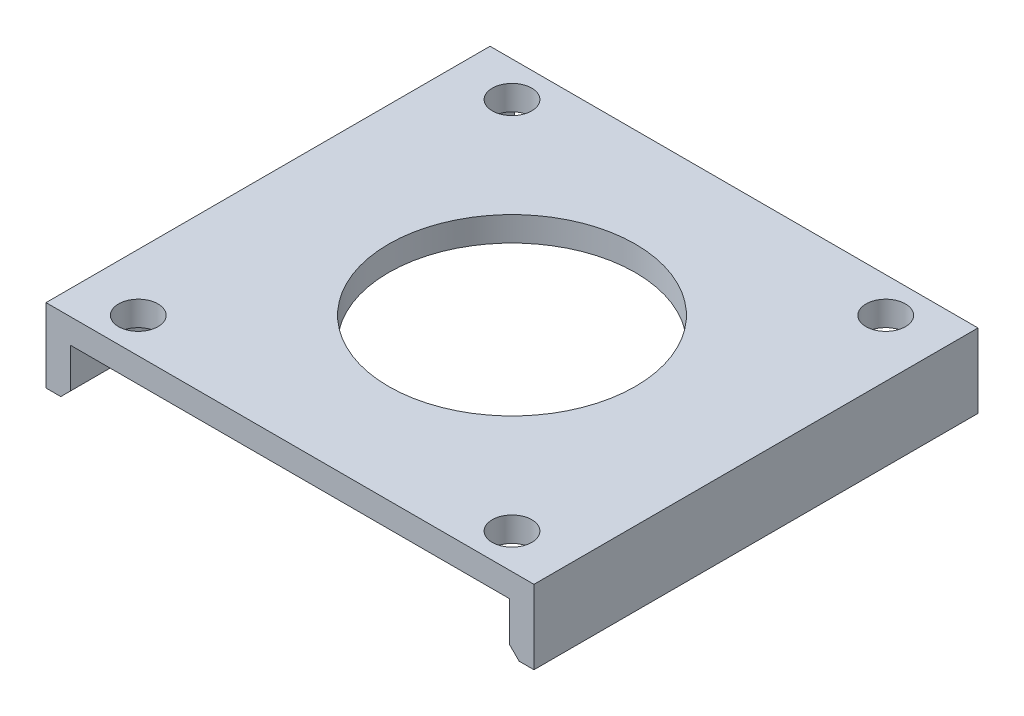
SolidWorks part; units mm, degrees
ref_plane "Front Plane" through (0, 0, 0) normal (0, 0, 1) x (1, 0, 0)
ref_plane "Top Plane" through (0, 0, 0) normal (0, 1, 0) x (1, 0, 0)
ref_plane "Right Plane" through (0, 0, 0) normal (1, 0, 0) x (0, 0, -1)
sketch "Sketch1" plane through (0, 0, 0) normal (0, 1, 0) x (1, 0, 0)
  line L0 (-37.875, 37.875) -> (37.875, -37.875) construction
  line L1 (-49.45, -45) -> (49.45, -45)
  line L2 (-49.45, -45) -> (-49.45, 45)
  line L3 (-49.45, 45) -> (49.45, 45)
  line L4 (49.45, -45) -> (49.45, 45)
  line L5 (-49.45, -45) -> (49.45, 45) construction
  line L6 (-49.45, 45) -> (49.45, -45) construction
  circle A0 centre (0, 0) radius 25
  circle A1 centre (-37.875, 37.875) radius 4
  circle A2 centre (37.875, 37.875) radius 4
  circle A3 centre (-37.875, -37.875) radius 4
  circle A4 centre (37.875, -37.875) radius 4
  point P0 (0, 0)
  point P16 (0, 0)
  dimension "D2" = 50
  dimension "D3" = 8
  dimension "D4" = 75.75
  dimension "D1" = 98.9
  dimension "D5" = 75.75
  dimension "D6" = 90
extrude "Boss-Extrude1" add sketch "Sketch1" along normal blind 5 contours L1 L4 L3 L2 A4 A3 A2 A1 A0
sketch "Sketch2" plane through (0, 0, 0) normal (0, -1, 0) x (1, 0, 0)
  line L0 (-49.45, -45) -> (49.45, -45) construction
  line L1 (-49.45, 45) -> (-44.45, 45)
  line L2 (-49.45, 45) -> (-49.45, -45)
  line L3 (-49.45, -45) -> (-44.45, -45)
  line L4 (-44.45, 45) -> (-44.45, -45)
  line L6 (49.45, 45) -> (44.45, 45)
  line L7 (49.45, 45) -> (49.45, -45)
  line L8 (49.45, -45) -> (44.45, -45)
  line L9 (44.45, 45) -> (44.45, -45)
  dimension "D1" = 5
  dimension "D2" = 5
extrude "Boss-Extrude2" add sketch "Sketch2" along normal blind 10
chamfer "Chamfer1" distance 2 angle 45 2 edges at (44.45, -10, 0) (-44.45, -10, 0)
